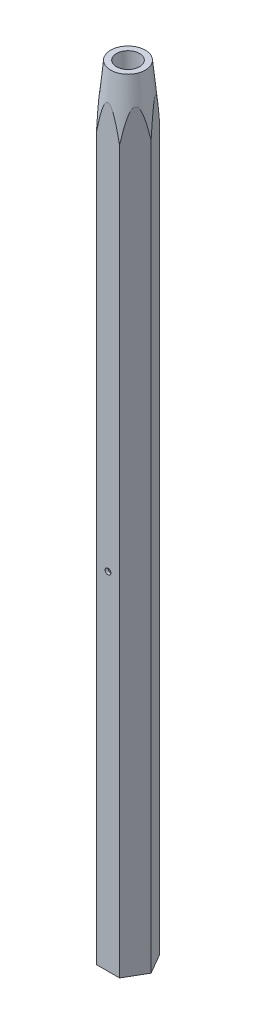
SolidWorks part; units mm, degrees
ref_plane "Alzado" through (0, 0, 0) normal (0, 0, 1) x (1, 0, 0)
ref_plane "Planta" through (0, 0, 0) normal (0, 1, 0) x (1, 0, 0)
ref_plane "Vista lateral" through (0, 0, 0) normal (1, 0, 0) x (0, 0, -1)
sketch "Croquis1" plane through (0, 0, 0) normal (0, 1, 0) x (1, 0, 0)
  circle A0 centre (0, 0) radius 4
  circle A1 centre (0, 0) radius 3
  dimension "D1" = 8
  dimension "D2" = 1
extrude "Saliente-Extruir1" add sketch "Croquis1" along normal blind 125
sketch "Croquis13" plane through (0, 0, 0) normal (0, 0, 1) x (1, 0, 0)
  line L0 (-4, 125) -> (-3, 135)
  line L1 (-3, 125) -> (-2.2679, 126.2679)
  line L3 (-3, 135) -> (-2, 135)
  line L4 (-2, 135) -> (-2, 127.2679)
  line L6 (-3, 125) -> (-4, 125)
  line L7 (3, 125) -> (-3, 125) construction
  line L8 (0, 125) -> (0, 133.0146) construction
  arc A0 (-2, 127.2679) -> (-2.2679, 126.2679) centre (-4, 127.2679) cw
  point P3 (-3, 125)
  dimension "D3" = 2
  dimension "D1" = 1
  dimension "D4" = 60
  dimension "D5" = 10
  dimension "D2" = 2
revolve "Revolución1" add sketch "Croquis13" angle 360 about L8
sketch "Croquis14" plane through (0, 0, 0) normal (0, -1, 0) x (1, 0, 0)
  line L1 (-4, 0) -> (-2, -3.4641)
  line L2 (-2, -3.4641) -> (2, -3.4641)
  line L3 (2, -3.4641) -> (4, 0)
  line L4 (4, 0) -> (2, 3.4641)
  line L5 (2, 3.4641) -> (-2, 3.4641)
  line L6 (-2, 3.4641) -> (-4, 0)
  circle A0 centre (0, 0) radius 3.4641 construction
  circle A1 centre (0, 0) radius 4 construction
  circle M1 centre (0, 0) radius 4
extrude "Cortar-Extruir1" cut sketch "Croquis14" against normal through all contours L2 M1 | L3 M1 | L4 M1 | L5 M1 | L6 M1 | L1 M1
fillet "Redondeo1" radius 4 1 edges at (0, 125, -3)
sketch "Croquis15" plane through (0, 0, 0) normal (0, -1, 0) x (1, 0, 0)
  circle A0 centre (0, 0) radius 3.25
  circle A1 centre (0, 0) radius 3.15
  dimension "D1" = 0.1
  dimension "D2" = 6.3
extrude "Cortar-Extruir2" cut sketch "Croquis15" against normal blind 0.05
sketch "Croquis17" plane through (0, 0, 3.4641) normal (0, 0, 1) x (1, 0, 0)
  line L0 (4.3606, 0) -> (-4.3606, 0) construction
  circle A0 centre (0, 60) radius 0.5
  dimension "D1" = 1
  dimension "D2" = 60
extrude "Cortar-Extruir3" cut sketch "Croquis17" against normal blind 1
equation "\"A\"= 80"
equation "\"B\"= 10"
equation "\"D5@Croquis13\"=\"B\""
